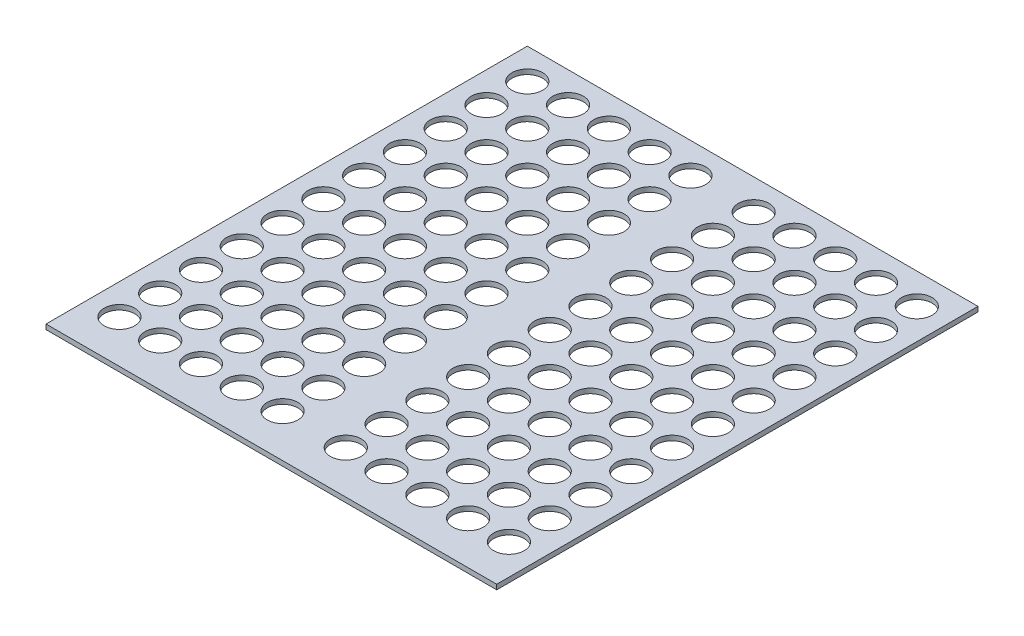
SolidWorks part; units mm, degrees
ref_plane "Front Plane" through (0, 0, 0) normal (0, 0, 1) x (1, 0, 0)
ref_plane "Top Plane" through (0, 0, 0) normal (0, 1, 0) x (1, 0, 0)
ref_plane "Right Plane" through (0, 0, 0) normal (1, 0, 0) x (0, 0, -1)
sketch "Sketch1" plane through (0, 0, 0) normal (0, 1, 0) x (1, 0, 0)
  line L1 (-55.25, 59) -> (55.25, 59)
  line L2 (-55.25, 59) -> (-55.25, -59)
  line L3 (-55.25, -59) -> (55.25, -59)
  line L4 (55.25, 59) -> (55.25, -59)
  line L5 (-55.25, 59) -> (55.25, -59) construction
  line L6 (-55.25, -59) -> (55.25, 59) construction
  point P0 (0, 0)
  dimension "D1" = 110.5
  dimension "D2" = 118
extrude "Boss-Extrude1" add sketch "Sketch1" along normal blind 1.2
sketch "Sketch2" plane through (0, 1.2, 0) normal (0, 1, 0) x (1, 0, 0)
  line L0 (55.25, 59) -> (-55.25, 59) construction
  line L1 (-55.25, 59) -> (-55.25, -59) construction
  line L2 (55.25, -59) -> (55.25, 59) construction
  circle A0 centre (-27.75, 51.5) radius 3.75
  circle A1 centre (-47.75, 51.5) radius 3.75
  circle A2 centre (17.75, 51.5) radius 3.75
  circle A3 centre (27.75, 51.5) radius 3.75
  circle A4 centre (47.75, 51.5) radius 3.75
  circle A5 centre (37.75, 51.5) radius 3.75
  circle A6 centre (-17.75, 51.5) radius 3.75
  circle A7 centre (7.75, 51.5) radius 3.75
  circle A8 centre (-7.75, 51.5) radius 3.75
  circle A9 centre (-37.75, 51.5) radius 3.75
  dimension "D2" = 7.5
  dimension "D3" = 10
  dimension "D6" = 10
  dimension "D8" = 10
  dimension "D5" = 10
  dimension "D7" = 10
  dimension "D11" = 10
  dimension "D1" = 7.5
  dimension "D4" = 7.5
  dimension "D9" = 10
  dimension "D10" = 10
  dimension "D13" = 7.5
  dimension "D14" = 7.5
extrude "Cut-Extrude1" cut sketch "Sketch2" against normal up to next
pattern_linear "LPattern1" count 11 spacing 10 along (0, 0, 1) of "Cut-Extrude1"
